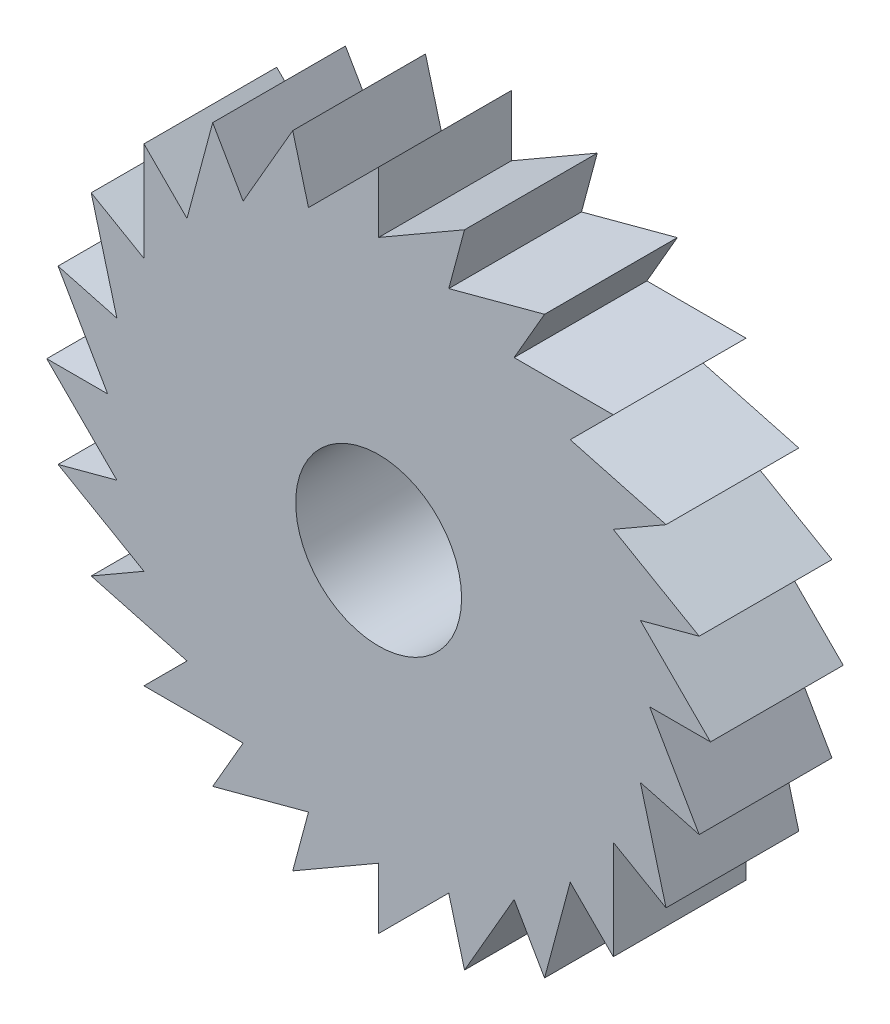
SolidWorks part; units mm, degrees
ref_plane "Front Plane" through (0, 0, 0) normal (0, 0, 1) x (1, 0, 0)
ref_plane "Top Plane" through (0, 0, 0) normal (0, 1, 0) x (1, 0, 0)
ref_plane "Right Plane" through (0, 0, 0) normal (1, 0, 0) x (0, 0, -1)
sketch "Sketch1" plane through (0, 0, 0) normal (0, 0, 1) x (1, 0, 0)
  line L0 (0, 0) -> (0, 12.7) construction
  line L1 (0, 0) -> (3.287, 12.2673) construction
  line L2 (0, 12.7) -> (0, 10.3695)
  line L3 (0, 10.3695) -> (3.287, 12.2673)
  line L4 (3.287, 12.2673) -> (2.6838, 10.0162)
  line L5 (2.6838, 10.0162) -> (6.35, 10.9985)
  line L6 (6.35, 10.9985) -> (5.1848, 8.9803)
  line L7 (5.1848, 8.9803) -> (8.9803, 8.9803)
  line L8 (8.9803, 8.9803) -> (7.3323, 7.3323)
  line L9 (7.3323, 7.3323) -> (10.9985, 6.35)
  line L10 (10.9985, 6.35) -> (8.9803, 5.1848)
  line L11 (8.9803, 5.1848) -> (12.2673, 3.287)
  line L12 (12.2673, 3.287) -> (10.0162, 2.6838)
  line L13 (10.0162, 2.6838) -> (12.7, 0)
  line L14 (12.7, 0) -> (10.3695, 0)
  line L15 (10.3695, 0) -> (12.2673, -3.287)
  line L16 (12.2673, -3.287) -> (10.0162, -2.6838)
  line L17 (10.0162, -2.6838) -> (10.9985, -6.35)
  line L18 (10.9985, -6.35) -> (8.9803, -5.1848)
  line L19 (8.9803, -5.1848) -> (8.9803, -8.9803)
  line L20 (8.9803, -8.9803) -> (7.3323, -7.3323)
  line L21 (7.3323, -7.3323) -> (6.35, -10.9985)
  line L22 (6.35, -10.9985) -> (5.1848, -8.9803)
  line L23 (5.1848, -8.9803) -> (3.287, -12.2673)
  line L24 (3.287, -12.2673) -> (2.6838, -10.0162)
  line L25 (2.6838, -10.0162) -> (0, -12.7)
  line L26 (0, -12.7) -> (0, -10.3695)
  line L27 (0, -10.3695) -> (-3.287, -12.2673)
  line L28 (-3.287, -12.2673) -> (-2.6838, -10.0162)
  line L29 (-2.6838, -10.0162) -> (-6.35, -10.9985)
  line L30 (-6.35, -10.9985) -> (-5.1848, -8.9803)
  line L31 (-5.1848, -8.9803) -> (-8.9803, -8.9803)
  line L32 (-8.9803, -8.9803) -> (-7.3323, -7.3323)
  line L33 (-7.3323, -7.3323) -> (-10.9985, -6.35)
  line L34 (-10.9985, -6.35) -> (-8.9803, -5.1848)
  line L35 (-8.9803, -5.1848) -> (-12.2673, -3.287)
  line L36 (-12.2673, -3.287) -> (-10.0162, -2.6838)
  line L37 (-10.0162, -2.6838) -> (-12.7, 0)
  line L38 (-12.7, 0) -> (-10.3695, 0)
  line L39 (-10.3695, 0) -> (-12.2673, 3.287)
  line L40 (-12.2673, 3.287) -> (-10.0162, 2.6838)
  line L41 (-10.0162, 2.6838) -> (-10.9985, 6.35)
  line L42 (-10.9985, 6.35) -> (-8.9803, 5.1848)
  line L43 (-8.9803, 5.1848) -> (-8.9803, 8.9803)
  line L44 (-8.9803, 8.9803) -> (-7.3323, 7.3323)
  line L45 (-7.3323, 7.3323) -> (-6.35, 10.9985)
  line L46 (-6.35, 10.9985) -> (-5.1848, 8.9803)
  line L47 (-5.1848, 8.9803) -> (-3.287, 12.2673)
  line L48 (-3.287, 12.2673) -> (-2.6838, 10.0162)
  line L49 (-2.6838, 10.0162) -> (0, 12.7)
  circle A0 centre (0, 0) radius 12.7 construction
  circle A1 centre (0, 0) radius 3.175
  dimension "D1" = 25.4
  dimension "D4" = 6.35
  dimension "D2" = 60
  dimension "D3" = 15
  dimension "D5" = 24
extrude "Boss-Extrude1" add sketch "Sketch1" along normal blind 5.08 contours L49 L48 L47 L46 L45 L44 L43 L42 L41 L40 L39 L38 L37 L36 L35 L34 L33 L32 L31 L30 L29 L28 L27 L26 L25 L24 L23 L22 L21 L20 L19 L18 L17 L16 L15 L14 L13 L12 L11 L10 L9 L8 L7 L6 L5 L4 L3 L2 A1
